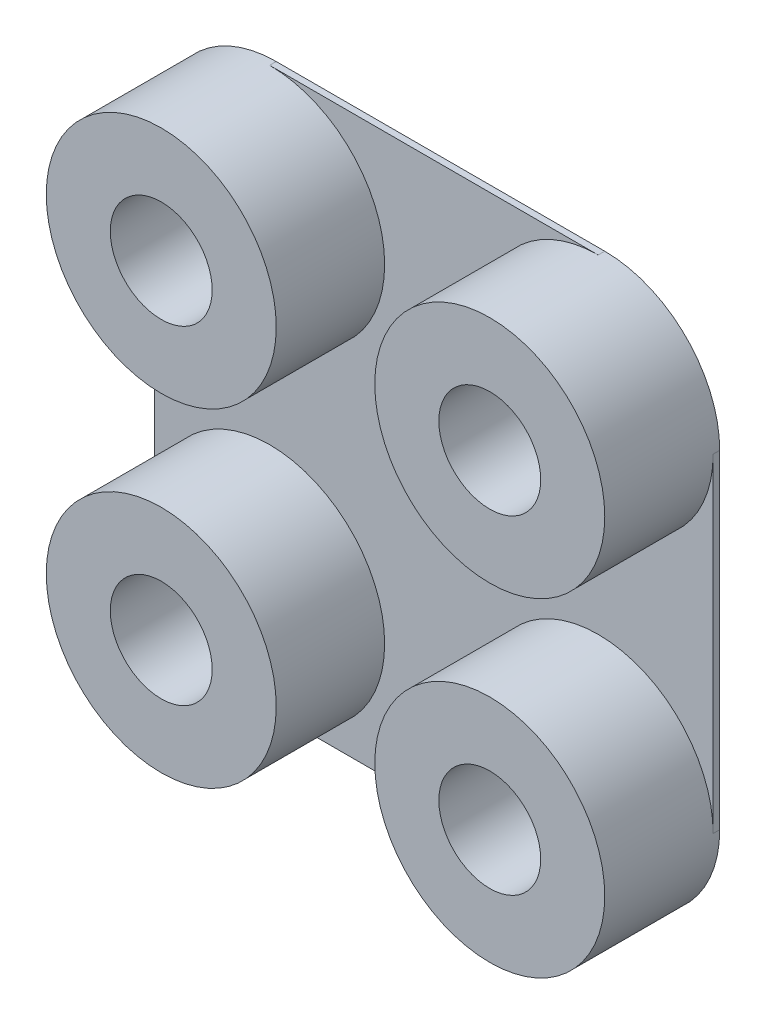
SolidWorks part; units mm, degrees
ref_plane "Front Plane" through (0, 0, 0) normal (0, 0, 1) x (1, 0, 0)
ref_plane "Top Plane" through (0, 0, 0) normal (0, 1, 0) x (1, 0, 0)
ref_plane "Right Plane" through (0, 0, 0) normal (1, 0, 0) x (0, 0, -1)
sketch "Sketch1" plane through (0, 0, 0) normal (0, 0, 1) x (1, 0, 0)
  circle A0 centre (0, 0) radius 3.5
  circle A1 centre (0, 0) radius 1.55
  circle A2 centre (10, 0) radius 3.5
  circle A3 centre (10, 0) radius 1.55
  circle A4 centre (10, 10) radius 3.5
  circle A5 centre (10, 10) radius 1.55
  circle A6 centre (0, 10) radius 3.5
  circle A7 centre (0, 10) radius 1.55
  dimension "D1" = 7
  dimension "D2" = 3.1
  dimension "D3" = 2
  dimension "D4" = 2
extrude "Boss-Extrude1" add sketch "Sketch1" along normal blind 3.5
sketch "Sketch2" plane through (0, 0, 0) normal (0, 0, 1) x (1, 0, 0)
  line L0 (-3.5, 10) -> (-3.5, 0)
  line L1 (0, 13.5) -> (10, 13.5)
  line L2 (13.5, 10) -> (13.5, 0)
  line L3 (10, -3.5) -> (0, -3.5)
  arc A0 (-3.5, 10) -> (0, 13.5) centre (0, 10) cw
  circle A1 centre (0, 10) radius 3.5 construction
  arc A2 (10, 13.5) -> (13.5, 10) centre (10, 10) cw
  circle A3 centre (10, 10) radius 3.5 construction
  arc A4 (13.5, 0) -> (10, -3.5) centre (10, 0) cw
  circle A5 centre (10, 0) radius 3.5 construction
  arc A6 (0, -3.5) -> (-3.5, 0) centre (0, 0) cw
  circle A7 centre (0, 0) radius 3.5 construction
extrude "Boss-Extrude2" add sketch "Sketch2" along normal blind 0.2
